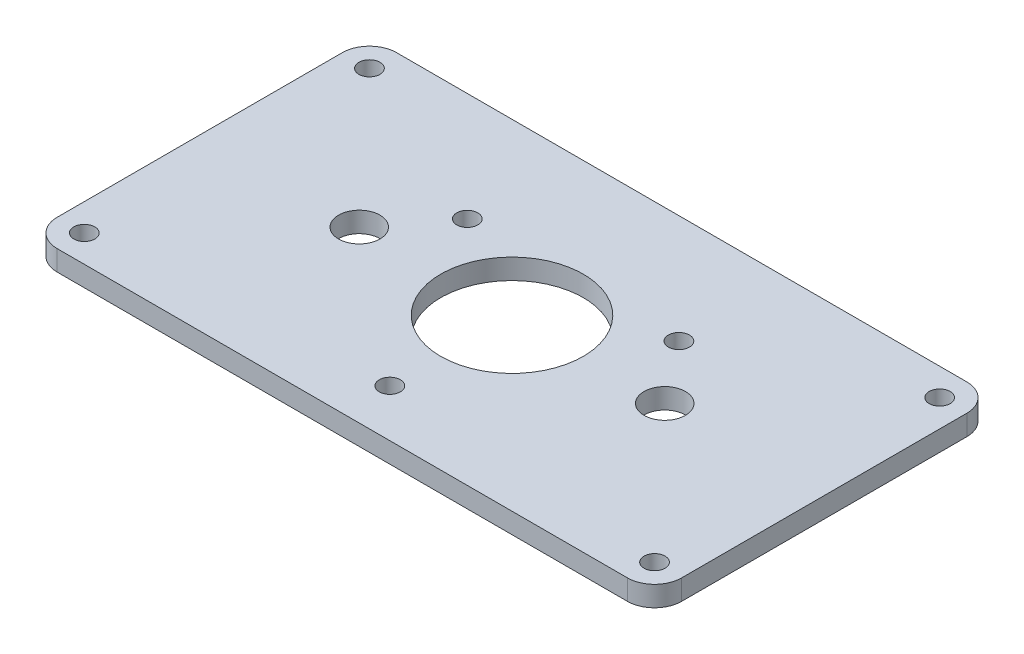
SolidWorks part; units mm, degrees
material "Thornel Mat VMA"
ref_plane "Front Plane" through (0, 0, 0) normal (0, 0, 1) x (1, 0, 0)
ref_plane "Top Plane" through (0, 0, 0) normal (0, 1, 0) x (1, 0, 0)
ref_plane "Right Plane" through (0, 0, 0) normal (1, 0, 0) x (0, 0, -1)
sketch "Sketch1" plane through (0, 0, 0) normal (0, 1, 0) x (1, 0, 0)
  line L0 (0, 0) -> (0, 79.06) construction
  line L1 (-46, -25) -> (46, -25)
  line L2 (-46, -25) -> (-46, 25)
  line L3 (-46, 25) -> (46, 25)
  line L4 (46, -25) -> (46, 25)
  line L5 (-46, -25) -> (46, 25) construction
  line L6 (-46, 25) -> (46, -25) construction
  line L7 (0, 0) -> (104.6127, 0) construction
  circle A0 centre (0, 0) radius 10.5
  circle A1 centre (42, 21) radius 1.55
  circle A2 centre (-42, 21) radius 1.55
  circle A3 centre (42, -21) radius 1.55
  circle A4 centre (-42, -21) radius 1.55
  circle A5 centre (0, 20) radius 2.05 construction
  circle A6 centre (0, -18) radius 1.55
  circle A7 centre (-15.5885, 9) radius 1.55
  circle A8 centre (17.3205, -10) radius 2.05 construction
  circle A9 centre (15.5885, 9) radius 1.55
  circle A10 centre (-17.3205, -10) radius 2.05 construction
  point P0 (0, 0)
  point P33 (0, 0)
  dimension "D3" = 3.1
  dimension "D4" = 4
  dimension "D5" = 4
  dimension "D6" = 21
  dimension "D7" = 4.1
  dimension "D8" = 20
  dimension "D9" = 18
  dimension "D1" = 50
  dimension "D2" = 92
  dimension "D10" = 3
extrude "Boss-Extrude1" add sketch "Sketch1" along normal blind 3
fillet "Fillet1" radius 4 4 edges at (46, 1.5, -25) (46, 1.5, 25) (-46, 1.5, 25) (-46, 1.5, -25)
sketch "草图1" plane through (0, 0, 0) normal (0, -1, 0) x (1, 0, 0)
  line L0 (-22.5, 0) -> (22.5, 0) construction
  circle A0 centre (-22.5, 0) radius 3.05
  circle A1 centre (22.5, 0) radius 3.05
  point P5 (0, 0)
  dimension "D1" = 6.1
  dimension "D2" = 6.1
  dimension "D3" = 22.5
extrude "切除-拉伸1" cut sketch "草图1" against normal blind 10
